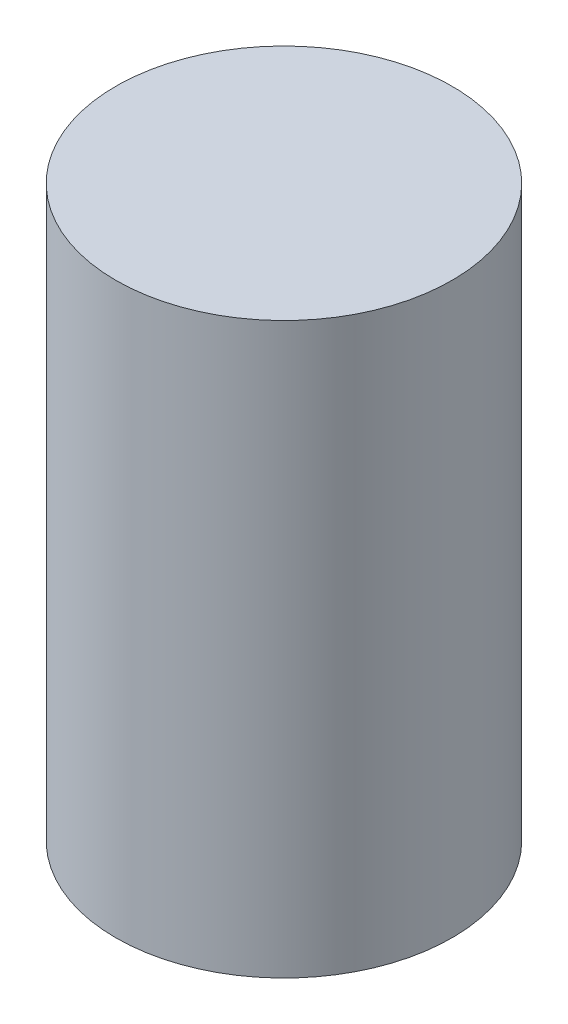
SolidWorks part; units mm, degrees
ref_plane "前视基准面" through (0, 0, 0) normal (0, 0, 1) x (1, 0, 0)
ref_plane "上视基准面" through (0, 0, 0) normal (0, 1, 0) x (1, 0, 0)
ref_plane "右视基准面" through (0, 0, 0) normal (1, 0, 0) x (0, 0, -1)
other "Configuration Table"
sketch "草图1" plane through (0, 0, 0) normal (0, 1, 0) x (1, 0, 0)
  circle A0 centre (0, 0) radius 7.5
  dimension "D1" = 15
extrude "凸台-拉伸1" add sketch "草图1" along normal blind 25.4
